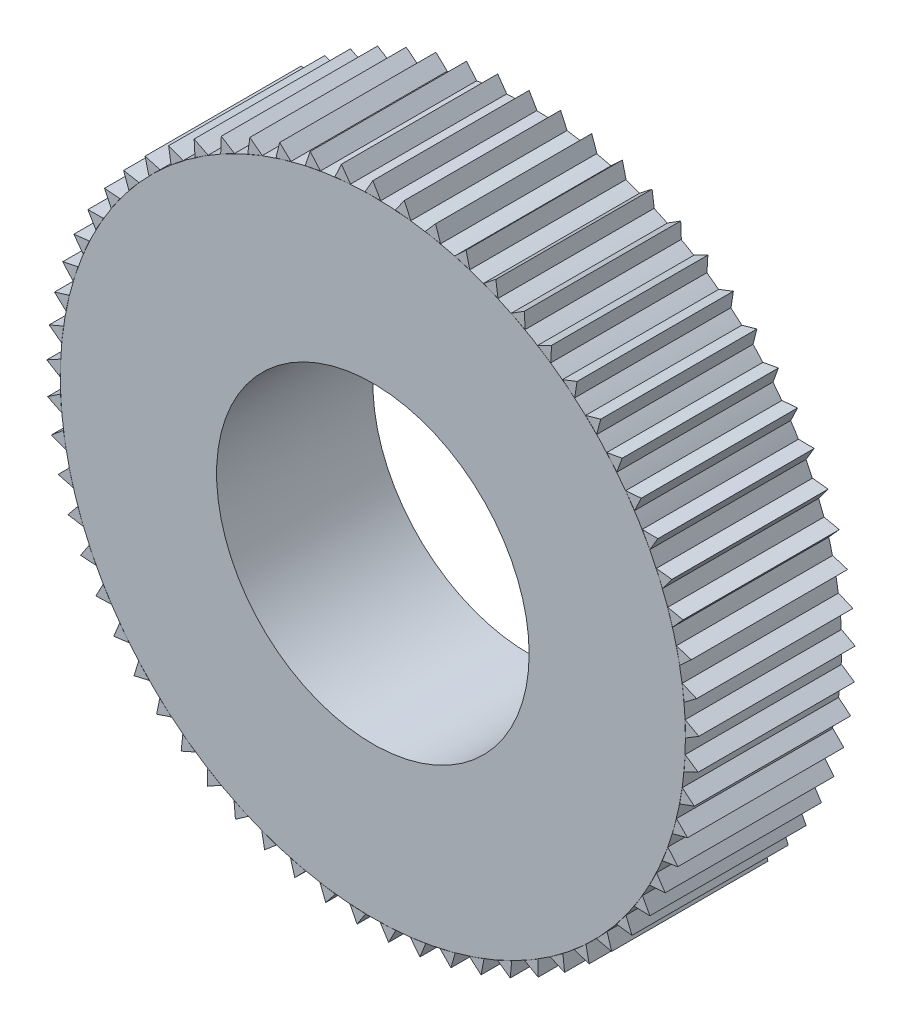
SolidWorks part; units mm, degrees
ref_plane "Front Plane" through (0, 0, 0) normal (0, 0, 1) x (1, 0, 0)
ref_plane "Top Plane" through (0, 0, 0) normal (0, 1, 0) x (1, 0, 0)
ref_plane "Right Plane" through (0, 0, 0) normal (1, 0, 0) x (0, 0, -1)
sketch "Sketch2" plane through (0, 0, 0) normal (0, 0, 1) x (1, 0, 0)
  circle A0 centre (0, 0) radius 50
  circle A1 centre (0, -0.896) radius 25
extrude "Boss-Extrude1" add sketch "Sketch2" along normal blind 25
sketch "Sketch3" plane through (0, 0, 25) normal (0, 0, 1) x (1, 0, 0)
  line L0 (0, 50) -> (1.25, 50)
  line L1 (0, 50) -> (-1.25, 50)
  line L2 (-1.25, 50) -> (0, 52.1651)
  line L3 (0, 52.1651) -> (1.25, 50)
  line L4 (5.0347, 51.9215) -> (6.0699, 49.6459)
  line L5 (4.8257, 49.7666) -> (6.0699, 49.6459)
  line L6 (4.8257, 49.7666) -> (3.5815, 49.8872)
  line L7 (3.5815, 49.8872) -> (5.0347, 51.9215)
  line L8 (10.0223, 51.1932) -> (10.833, 48.8283)
  line L9 (9.6063, 49.0685) -> (10.833, 48.8283)
  line L10 (9.6063, 49.0685) -> (8.3796, 49.3087)
  line L11 (8.3796, 49.3087) -> (10.0223, 51.1932)
  line L12 (14.9164, 49.987) -> (15.4951, 47.5549)
  line L13 (14.2973, 47.9123) -> (15.4951, 47.5549)
  line L14 (14.2973, 47.9123) -> (13.0995, 48.2697)
  line L15 (13.0995, 48.2697) -> (14.9164, 49.987)
  line L16 (19.6712, 48.314) -> (20.0125, 45.8374)
  line L17 (18.8547, 46.3087) -> (20.0125, 45.8374)
  line L18 (18.8547, 46.3087) -> (17.697, 46.7801)
  line L19 (17.697, 46.7801) -> (19.6712, 48.314)
  line L20 (24.2423, 46.1899) -> (24.343, 43.6919)
  line L21 (23.2362, 44.2728) -> (24.343, 43.6919)
  line L22 (23.2362, 44.2728) -> (22.1293, 44.8537)
  line L23 (22.1293, 44.8537) -> (24.2423, 46.1899)
  line L24 (28.5871, 43.6345) -> (28.4462, 41.1385)
  line L25 (27.4006, 41.8235) -> (28.4462, 41.1385)
  line L26 (27.4006, 41.8235) -> (26.355, 42.5085)
  line L27 (26.355, 42.5085) -> (28.5871, 43.6345)
  line L28 (32.665, 40.6718) -> (32.2839, 38.201)
  line L29 (31.3093, 38.9837) -> (32.2839, 38.201)
  line L30 (31.3093, 38.9837) -> (30.3347, 39.7664)
  line L31 (30.3347, 39.7664) -> (32.665, 40.6718)
  line L32 (36.4379, 37.3293) -> (35.8201, 34.9068)
  line L33 (34.9256, 35.7799) -> (35.8201, 34.9068)
  line L34 (34.9256, 35.7799) -> (34.0311, 36.6531)
  line L35 (34.0311, 36.6531) -> (36.4379, 37.3293)
  line L36 (39.8706, 33.6382) -> (39.0218, 31.2867)
  line L37 (38.2158, 32.2421) -> (39.0218, 31.2867)
  line L38 (38.2158, 32.2421) -> (37.4097, 33.1975)
  line L39 (37.4097, 33.1975) -> (39.8706, 33.6382)
  line L40 (42.931, 29.6331) -> (41.8593, 27.3745)
  line L41 (41.1492, 28.4032) -> (41.8593, 27.3745)
  line L42 (41.1492, 28.4032) -> (40.4391, 29.432)
  line L43 (40.4391, 29.432) -> (42.931, 29.6331)
  line L44 (45.5906, 25.3514) -> (44.3059, 23.2067)
  line L45 (43.6984, 24.2992) -> (44.3059, 23.2067)
  line L46 (43.6984, 24.2992) -> (43.0909, 25.3916)
  line L47 (43.0909, 25.3916) -> (45.5906, 25.3514)
  line L48 (47.8245, 20.8329) -> (46.3388, 18.8222)
  line L49 (45.8396, 19.9682) -> (46.3388, 18.8222)
  line L50 (45.8396, 19.9682) -> (45.3404, 21.1142)
  line L51 (45.3404, 21.1142) -> (47.8245, 20.8329)
  line L52 (49.6119, 16.1199) -> (47.9391, 14.262)
  line L53 (47.5528, 15.4508) -> (47.9391, 14.262)
  line L54 (47.5528, 15.4508) -> (47.1666, 16.6397)
  line L55 (47.1666, 16.6397) -> (49.6119, 16.1199)
  line L56 (50.9361, 11.2564) -> (49.0918, 9.5687)
  line L57 (48.8221, 10.7892) -> (49.0918, 9.5687)
  line L58 (48.8221, 10.7892) -> (48.5523, 12.0098)
  line L59 (48.5523, 12.0098) -> (50.9361, 11.2564)
  line L60 (51.7847, 6.2878) -> (49.7861, 4.7859)
  line L61 (49.6354, 6.0268) -> (49.7861, 4.7859)
  line L62 (49.6354, 6.0268) -> (49.4848, 7.2677)
  line L63 (49.4848, 7.2677) -> (51.7847, 6.2878)
  line L64 (52.1498, 1.2605) -> (50.0156, -0.0414)
  line L65 (49.9854, 1.2082) -> (50.0156, -0.0414)
  line L66 (49.9854, 1.2082) -> (49.9552, 2.4578)
  line L67 (49.9552, 2.4578) -> (52.1498, 1.2605)
  line L68 (52.028, -3.7786) -> (49.7781, -4.8685)
  line L69 (49.8687, -3.6217) -> (49.7781, -4.8685)
  line L70 (49.8687, -3.6217) -> (49.9592, -2.375)
  line L71 (49.9592, -2.375) -> (52.028, -3.7786)
  line L72 (51.4205, -8.7824) -> (49.0759, -9.65)
  line L73 (49.2863, -8.4179) -> (49.0759, -9.65)
  line L74 (49.2863, -8.4179) -> (49.4968, -7.1857)
  line L75 (49.4968, -7.1857) -> (51.4205, -8.7824)
  line L76 (50.3328, -13.7041) -> (47.9154, -14.3415)
  line L77 (48.2438, -13.1354) -> (47.9154, -14.3415)
  line L78 (48.2438, -13.1354) -> (48.5722, -11.9293)
  line L79 (48.5722, -11.9293) -> (50.3328, -13.7041)
  line L80 (48.7752, -18.498) -> (46.3076, -18.899)
  line L81 (46.7508, -17.7302) -> (46.3076, -18.899)
  line L82 (46.7508, -17.7302) -> (47.1941, -16.5615)
  line L83 (47.1941, -16.5615) -> (48.7752, -18.498)
  line L84 (46.7622, -23.1191) -> (44.2674, -23.2801)
  line L85 (44.8213, -22.1596) -> (44.2674, -23.2801)
  line L86 (44.8213, -22.1596) -> (45.3753, -21.039)
  line L87 (45.3753, -21.039) -> (46.7622, -23.1191)
  line L88 (44.3125, -27.5244) -> (41.8138, -27.4438)
  line L89 (42.4734, -26.382) -> (41.8138, -27.4438)
  line L90 (42.4734, -26.382) -> (43.1329, -25.3202)
  line L91 (43.1329, -25.3202) -> (44.3125, -27.5244)
  line L92 (41.4492, -31.6727) -> (38.9699, -31.3513)
  line L93 (39.7289, -30.3581) -> (38.9699, -31.3513)
  line L94 (39.7289, -30.3581) -> (40.4878, -29.3649)
  line L95 (40.4878, -29.3649) -> (41.4492, -31.6727)
  line L96 (38.1988, -35.5252) -> (35.7622, -34.9661)
  line L97 (36.6134, -34.0508) -> (35.7622, -34.9661)
  line L98 (36.6134, -34.0508) -> (37.4647, -33.1355)
  line L99 (37.4647, -33.1355) -> (38.1988, -35.5252)
  line L100 (34.5918, -39.0461) -> (32.2205, -38.2544)
  line L101 (33.1561, -37.4255) -> (32.2205, -38.2544)
  line L102 (33.1561, -37.4255) -> (34.0918, -36.5966)
  line L103 (34.0918, -36.5966) -> (34.5918, -39.0461)
  line L104 (30.6619, -42.2024) -> (28.378, -41.1856)
  line L105 (29.3893, -40.4508) -> (28.378, -41.1856)
  line L106 (29.3893, -40.4508) -> (30.4005, -39.7161)
  line L107 (30.4005, -39.7161) -> (30.6619, -42.2024)
  line L108 (26.4456, -44.9647) -> (24.2705, -43.7322)
  line L109 (25.348, -43.0985) -> (24.2705, -43.7322)
  line L110 (25.348, -43.0985) -> (26.4255, -42.4648)
  line L111 (26.4255, -42.4648) -> (26.4456, -44.9647)
  line L112 (21.9824, -47.3072) -> (19.9365, -45.8705)
  line L113 (21.0701, -45.3437) -> (19.9365, -45.8705)
  line L114 (21.0701, -45.3437) -> (22.2036, -44.817)
  line L115 (22.2036, -44.817) -> (21.9824, -47.3072)
  line L116 (17.314, -49.2079) -> (15.4163, -47.5805)
  line L117 (16.5954, -47.1656) -> (15.4163, -47.5805)
  line L118 (16.5954, -47.1656) -> (17.7745, -46.7507)
  line L119 (17.7745, -46.7507) -> (17.314, -49.2079)
  line L120 (12.4839, -50.6492) -> (10.7521, -48.8462)
  line L121 (11.9658, -48.5471) -> (10.7521, -48.8462)
  line L122 (11.9658, -48.5471) -> (13.1795, -48.2479)
  line L123 (13.1795, -48.2479) -> (12.4839, -50.6492)
  line L124 (7.5373, -51.6177) -> (5.9876, -49.6559)
  line L125 (7.2245, -49.4753) -> (5.9876, -49.6559)
  line L126 (7.2245, -49.4753) -> (8.4613, -49.2947)
  line L127 (8.4613, -49.2947) -> (7.5373, -51.6177)
  line L128 (2.5203, -52.1041) -> (1.1671, -50.002)
  line L129 (2.4157, -49.9416) -> (1.1671, -50.002)
  line L130 (2.4157, -49.9416) -> (3.6642, -49.8812)
  line L131 (3.6642, -49.8812) -> (2.5203, -52.1041)
  line L132 (-2.5203, -52.1041) -> (-3.6642, -49.8812)
  line L133 (-2.4157, -49.9416) -> (-3.6642, -49.8812)
  line L134 (-2.4157, -49.9416) -> (-1.1671, -50.002)
  line L135 (-1.1671, -50.002) -> (-2.5203, -52.1041)
  line L136 (-7.5373, -51.6177) -> (-8.4613, -49.2947)
  line L137 (-7.2245, -49.4753) -> (-8.4613, -49.2947)
  line L138 (-7.2245, -49.4753) -> (-5.9876, -49.6559)
  line L139 (-5.9876, -49.6559) -> (-7.5373, -51.6177)
  line L140 (-12.4839, -50.6492) -> (-13.1795, -48.2479)
  line L141 (-11.9658, -48.5471) -> (-13.1795, -48.2479)
  line L142 (-11.9658, -48.5471) -> (-10.7521, -48.8462)
  line L143 (-10.7521, -48.8462) -> (-12.4839, -50.6492)
  line L144 (-17.314, -49.2079) -> (-17.7745, -46.7507)
  line L145 (-16.5954, -47.1656) -> (-17.7745, -46.7507)
  line L146 (-16.5954, -47.1656) -> (-15.4163, -47.5805)
  line L147 (-15.4163, -47.5805) -> (-17.314, -49.2079)
  line L148 (-21.9824, -47.3072) -> (-22.2036, -44.817)
  line L149 (-21.0701, -45.3437) -> (-22.2036, -44.817)
  line L150 (-21.0701, -45.3437) -> (-19.9365, -45.8705)
  line L151 (-19.9365, -45.8705) -> (-21.9824, -47.3072)
  line L152 (-26.4456, -44.9647) -> (-26.4255, -42.4648)
  line L153 (-25.348, -43.0985) -> (-26.4255, -42.4648)
  line L154 (-25.348, -43.0985) -> (-24.2705, -43.7322)
  line L155 (-24.2705, -43.7322) -> (-26.4456, -44.9647)
  line L156 (-30.6619, -42.2024) -> (-30.4005, -39.7161)
  line L157 (-29.3893, -40.4508) -> (-30.4005, -39.7161)
  line L158 (-29.3893, -40.4508) -> (-28.378, -41.1856)
  line L159 (-28.378, -41.1856) -> (-30.6619, -42.2024)
  line L160 (-34.5918, -39.0461) -> (-34.0918, -36.5966)
  line L161 (-33.1561, -37.4255) -> (-34.0918, -36.5966)
  line L162 (-33.1561, -37.4255) -> (-32.2205, -38.2544)
  line L163 (-32.2205, -38.2544) -> (-34.5918, -39.0461)
  line L164 (-38.1988, -35.5252) -> (-37.4647, -33.1355)
  line L165 (-36.6134, -34.0508) -> (-37.4647, -33.1355)
  line L166 (-36.6134, -34.0508) -> (-35.7622, -34.9661)
  line L167 (-35.7622, -34.9661) -> (-38.1988, -35.5252)
  line L168 (-41.4492, -31.6727) -> (-40.4878, -29.3649)
  line L169 (-39.7289, -30.3581) -> (-40.4878, -29.3649)
  line L170 (-39.7289, -30.3581) -> (-38.9699, -31.3513)
  line L171 (-38.9699, -31.3513) -> (-41.4492, -31.6727)
  line L172 (-44.3125, -27.5244) -> (-43.1329, -25.3202)
  line L173 (-42.4734, -26.382) -> (-43.1329, -25.3202)
  line L174 (-42.4734, -26.382) -> (-41.8138, -27.4438)
  line L175 (-41.8138, -27.4438) -> (-44.3125, -27.5244)
  line L176 (-46.7622, -23.1191) -> (-45.3753, -21.039)
  line L177 (-44.8213, -22.1596) -> (-45.3753, -21.039)
  line L178 (-44.8213, -22.1596) -> (-44.2674, -23.2801)
  line L179 (-44.2674, -23.2801) -> (-46.7622, -23.1191)
  line L180 (-48.7752, -18.498) -> (-47.1941, -16.5615)
  line L181 (-46.7508, -17.7302) -> (-47.1941, -16.5615)
  line L182 (-46.7508, -17.7302) -> (-46.3076, -18.899)
  line L183 (-46.3076, -18.899) -> (-48.7752, -18.498)
  line L184 (-50.3328, -13.7041) -> (-48.5722, -11.9293)
  line L185 (-48.2438, -13.1354) -> (-48.5722, -11.9293)
  line L186 (-48.2438, -13.1354) -> (-47.9154, -14.3415)
  line L187 (-47.9154, -14.3415) -> (-50.3328, -13.7041)
  line L188 (-51.4205, -8.7824) -> (-49.4968, -7.1857)
  line L189 (-49.2863, -8.4179) -> (-49.4968, -7.1857)
  line L190 (-49.2863, -8.4179) -> (-49.0759, -9.65)
  line L191 (-49.0759, -9.65) -> (-51.4205, -8.7824)
  line L192 (-52.028, -3.7786) -> (-49.9592, -2.375)
  line L193 (-49.8687, -3.6217) -> (-49.9592, -2.375)
  line L194 (-49.8687, -3.6217) -> (-49.7781, -4.8685)
  line L195 (-49.7781, -4.8685) -> (-52.028, -3.7786)
  line L196 (-52.1498, 1.2605) -> (-49.9552, 2.4578)
  line L197 (-49.9854, 1.2082) -> (-49.9552, 2.4578)
  line L198 (-49.9854, 1.2082) -> (-50.0156, -0.0414)
  line L199 (-50.0156, -0.0414) -> (-52.1498, 1.2605)
  line L200 (-51.7847, 6.2878) -> (-49.4848, 7.2677)
  line L201 (-49.6354, 6.0268) -> (-49.4848, 7.2677)
  line L202 (-49.6354, 6.0268) -> (-49.7861, 4.7859)
  line L203 (-49.7861, 4.7859) -> (-51.7847, 6.2878)
  line L204 (-50.9361, 11.2564) -> (-48.5523, 12.0098)
  line L205 (-48.8221, 10.7892) -> (-48.5523, 12.0098)
  line L206 (-48.8221, 10.7892) -> (-49.0918, 9.5687)
  line L207 (-49.0918, 9.5687) -> (-50.9361, 11.2564)
  line L208 (-49.6119, 16.1199) -> (-47.1666, 16.6397)
  line L209 (-47.5528, 15.4508) -> (-47.1666, 16.6397)
  line L210 (-47.5528, 15.4508) -> (-47.9391, 14.262)
  line L211 (-47.9391, 14.262) -> (-49.6119, 16.1199)
  line L212 (-47.8245, 20.8329) -> (-45.3404, 21.1142)
  line L213 (-45.8396, 19.9682) -> (-45.3404, 21.1142)
  line L214 (-45.8396, 19.9682) -> (-46.3388, 18.8222)
  line L215 (-46.3388, 18.8222) -> (-47.8245, 20.8329)
  line L216 (-45.5906, 25.3514) -> (-43.0909, 25.3916)
  line L217 (-43.6984, 24.2992) -> (-43.0909, 25.3916)
  line L218 (-43.6984, 24.2992) -> (-44.3059, 23.2067)
  line L219 (-44.3059, 23.2067) -> (-45.5906, 25.3514)
  line L220 (-42.931, 29.6331) -> (-40.4391, 29.432)
  line L221 (-41.1492, 28.4032) -> (-40.4391, 29.432)
  line L222 (-41.1492, 28.4032) -> (-41.8593, 27.3745)
  line L223 (-41.8593, 27.3745) -> (-42.931, 29.6331)
  line L224 (-39.8706, 33.6382) -> (-37.4097, 33.1975)
  line L225 (-38.2158, 32.2421) -> (-37.4097, 33.1975)
  line L226 (-38.2158, 32.2421) -> (-39.0218, 31.2867)
  line L227 (-39.0218, 31.2867) -> (-39.8706, 33.6382)
  line L228 (-36.4379, 37.3293) -> (-34.0311, 36.6531)
  line L229 (-34.9256, 35.7799) -> (-34.0311, 36.6531)
  line L230 (-34.9256, 35.7799) -> (-35.8201, 34.9068)
  line L231 (-35.8201, 34.9068) -> (-36.4379, 37.3293)
  line L232 (-32.665, 40.6718) -> (-30.3347, 39.7664)
  line L233 (-31.3093, 38.9837) -> (-30.3347, 39.7664)
  line L234 (-31.3093, 38.9837) -> (-32.2839, 38.201)
  line L235 (-32.2839, 38.201) -> (-32.665, 40.6718)
  line L236 (-28.5871, 43.6345) -> (-26.355, 42.5085)
  line L237 (-27.4006, 41.8235) -> (-26.355, 42.5085)
  line L238 (-27.4006, 41.8235) -> (-28.4462, 41.1385)
  line L239 (-28.4462, 41.1385) -> (-28.5871, 43.6345)
  line L240 (-24.2423, 46.1899) -> (-22.1293, 44.8537)
  line L241 (-23.2362, 44.2728) -> (-22.1293, 44.8537)
  line L242 (-23.2362, 44.2728) -> (-24.343, 43.6919)
  line L243 (-24.343, 43.6919) -> (-24.2423, 46.1899)
  line L244 (-19.6712, 48.314) -> (-17.697, 46.7801)
  line L245 (-18.8547, 46.3087) -> (-17.697, 46.7801)
  line L246 (-18.8547, 46.3087) -> (-20.0125, 45.8374)
  line L247 (-20.0125, 45.8374) -> (-19.6712, 48.314)
  line L248 (-14.9164, 49.987) -> (-13.0995, 48.2697)
  line L249 (-14.2973, 47.9123) -> (-13.0995, 48.2697)
  line L250 (-14.2973, 47.9123) -> (-15.4951, 47.5549)
  line L251 (-15.4951, 47.5549) -> (-14.9164, 49.987)
  line L252 (-10.0223, 51.1932) -> (-8.3796, 49.3087)
  line L253 (-9.6063, 49.0685) -> (-8.3796, 49.3087)
  line L254 (-9.6063, 49.0685) -> (-10.833, 48.8283)
  line L255 (-10.833, 48.8283) -> (-10.0223, 51.1932)
  line L256 (-5.0347, 51.9215) -> (-3.5815, 49.8872)
  line L257 (-4.8257, 49.7666) -> (-3.5815, 49.8872)
  line L258 (-4.8257, 49.7666) -> (-6.0699, 49.6459)
  line L259 (-6.0699, 49.6459) -> (-5.0347, 51.9215)
  circle A0 centre (0, 0) radius 50 construction
  dimension "D1" = 1.25
  dimension "D2" = 1.25
  dimension "D3" = 300
  dimension "D4" = 120
extrude "Boss-Extrude2" add sketch "Sketch3" against normal blind 25 separate body
